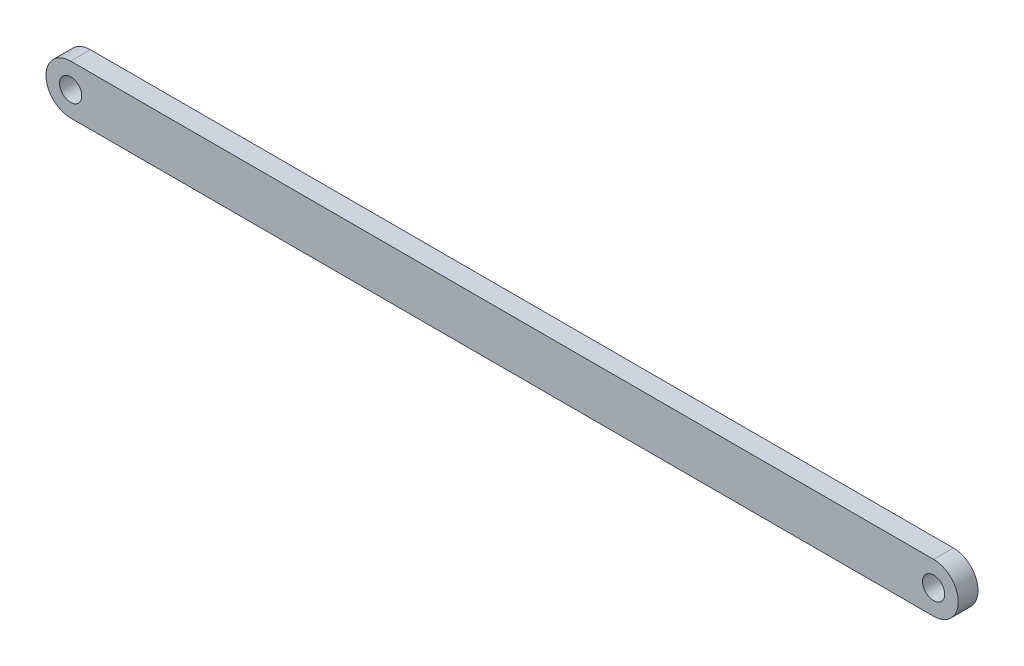
SolidWorks part; units mm, degrees
material "PET"
ref_plane "Front Plane" through (0, 0, 0) normal (0, 0, 1) x (1, 0, 0)
ref_plane "Top Plane" through (0, 0, 0) normal (0, 1, 0) x (1, 0, 0)
ref_plane "Right Plane" through (0, 0, 0) normal (1, 0, 0) x (0, 0, -1)
sketch "Sketch1" plane through (0, 0, 0) normal (0, 0, 1) x (1, 0, 0)
  line L0 (0, 0) -> (175, 0) construction
  line L1 (0, 5) -> (175, 5)
  line L2 (0, -5) -> (175, -5)
  arc A0 (0, 5) -> (0, -5) centre (0, 0) ccw
  arc A1 (175, -5) -> (175, 5) centre (175, 0) ccw
  circle A2 centre (0, 0) radius 2.25
  circle A3 centre (175, 0) radius 2.25
  point P3 (87.5, 0)
  dimension "D1" = 5
  dimension "D3" = 4.5
  dimension "D4" = 4.5
  dimension "D2" = 175
extrude "Boss-Extrude1" add sketch "Sketch1" along normal mid plane 4
